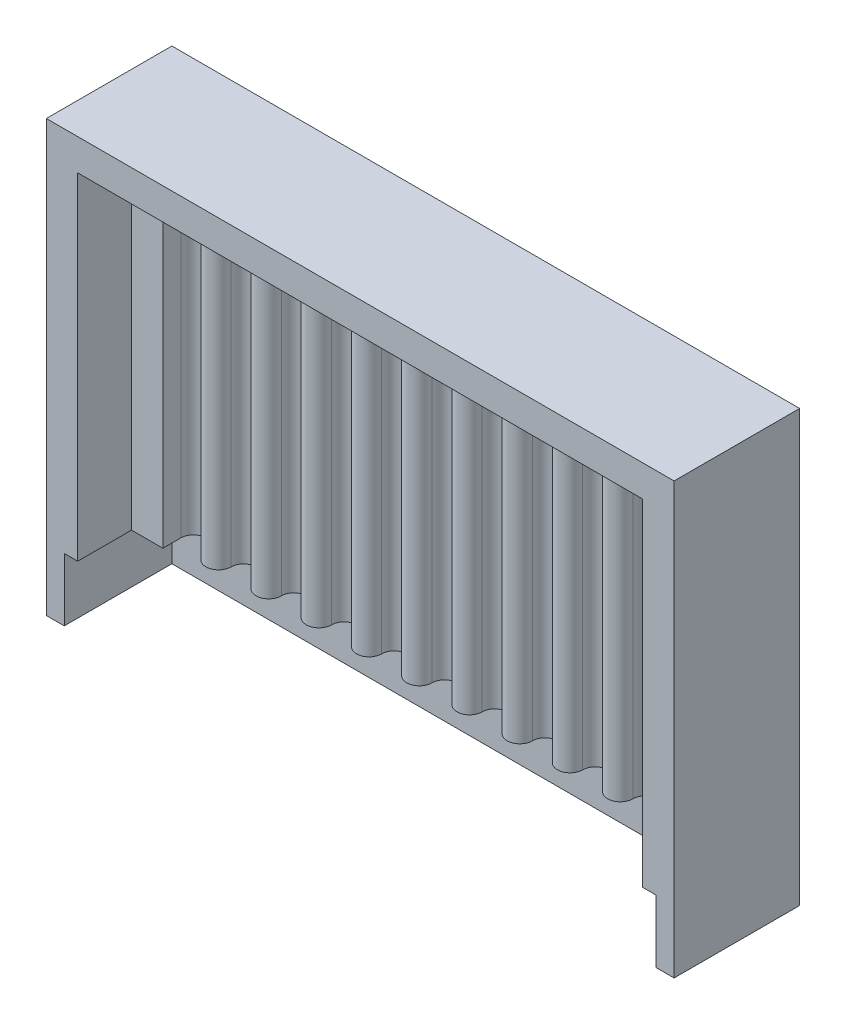
SolidWorks part; units mm, degrees
ref_plane "前视基准面" through (0, 0, 0) normal (0, 0, 1) x (1, 0, 0)
ref_plane "上视基准面" through (0, 0, 0) normal (0, 1, 0) x (1, 0, 0)
ref_plane "右视基准面" through (0, 0, 0) normal (1, 0, 0) x (0, 0, -1)
other "Configuration Table"
sketch "草图1" plane through (0, 0, 0) normal (0, 0, 1) x (1, 0, 0)
  line L1 (-17.5, 12) -> (17.5, 12)
  line L2 (-17.5, 12) -> (-17.5, -12)
  line L3 (-17.5, -12) -> (17.5, -12)
  line L4 (17.5, 12) -> (17.5, -12)
  line L5 (-17.5, 12) -> (17.5, -12) construction
  line L6 (-17.5, -12) -> (17.5, 12) construction
  point P0 (0, 0)
extrude "凸台-拉伸1" add sketch "草图1" along normal blind 7
sketch "草图2" plane through (0, 0, 7) normal (0, 0, 1) x (1, 0, 0)
  line L1 (-15.75, 10.25) -> (15.75, 10.25)
  line L2 (-15.75, 10.25) -> (-15.75, -10.25)
  line L3 (-15.75, -10.25) -> (15.75, -10.25)
  line L4 (15.75, 10.25) -> (15.75, -10.25)
  line L5 (-15.75, 10.25) -> (15.75, -10.25) construction
  line L6 (-15.75, -10.25) -> (15.75, 10.25) construction
  point P0 (0, 0)
  dimension "D1" = 20.5
  dimension "D2" = 31.5
extrude "切除-拉伸1" cut sketch "草图2" against normal blind 3
sketch "草图3" plane through (0, 0, 4) normal (0, 0, 1) x (1, 0, 0)
  line L1 (-14, 8.5) -> (14, 8.5)
  line L2 (-14, 8.5) -> (-14, -8.5)
  line L3 (-14, -8.5) -> (14, -8.5)
  line L4 (14, 8.5) -> (14, -8.5)
  line L5 (-14, 8.5) -> (14, -8.5) construction
  line L6 (-14, -8.5) -> (14, 8.5) construction
  point P0 (0, 0)
extrude "切除-拉伸2" cut sketch "草图3" against normal blind 2
sketch "草图4" plane through (0, 8.5, 0) normal (0, -1, 0) x (1, 0, 0)
  line L0 (-15, 3) -> (-15, 1)
  line L1 (-14, 4) -> (14, 4) construction
  line L2 (-14, 4) -> (-14, 2) construction
  line L3 (-14, 2) -> (14, 2) construction
  line L4 (14, 4) -> (14, 2) construction
  line L5 (-14, 3) -> (-13.6627, 3) construction
  line L6 (-15, 1) -> (15, 1)
  line L7 (15, 1) -> (15, 3)
  line L8 (15, 3) -> (14, 3)
  line L9 (-14, 3) -> (-15, 3)
  arc A0 (-14, 3) -> (-12.6, 3) centre (-13.3, 3) ccw
  arc A1 (-11.2, 3) -> (-12.6, 3) centre (-11.9, 3) ccw
  arc A2 (-8.4, 3) -> (-9.8, 3) centre (-9.1, 3) ccw
  arc A3 (-11.2, 3) -> (-9.8, 3) centre (-10.5, 3) ccw
  arc A4 (-5.6, 3) -> (-7, 3) centre (-6.3, 3) ccw
  arc A5 (-8.4, 3) -> (-7, 3) centre (-7.7, 3) ccw
  arc A6 (-2.8, 3) -> (-4.2, 3) centre (-3.5, 3) ccw
  arc A7 (-5.6, 3) -> (-4.2, 3) centre (-4.9, 3) ccw
  arc A8 (0, 3) -> (-1.4, 3) centre (-0.7, 3) ccw
  arc A9 (-2.8, 3) -> (-1.4, 3) centre (-2.1, 3) ccw
  arc A10 (2.8, 3) -> (1.4, 3) centre (2.1, 3) ccw
  arc A11 (0, 3) -> (1.4, 3) centre (0.7, 3) ccw
  arc A12 (5.6, 3) -> (4.2, 3) centre (4.9, 3) ccw
  arc A13 (2.8, 3) -> (4.2, 3) centre (3.5, 3) ccw
  arc A14 (8.4, 3) -> (7, 3) centre (7.7, 3) ccw
  arc A15 (5.6, 3) -> (7, 3) centre (6.3, 3) ccw
  arc A16 (11.2, 3) -> (9.8, 3) centre (10.5, 3) ccw
  arc A17 (8.4, 3) -> (9.8, 3) centre (9.1, 3) ccw
  arc A18 (14, 3) -> (12.6, 3) centre (13.3, 3) ccw
  arc A19 (11.2, 3) -> (12.6, 3) centre (11.9, 3) ccw
  point P4 (-14, 3)
  point P9 (-13.3, 3)
  point P12 (-11.9, 3)
  dimension "D2" = 1.4
  dimension "D3" = 10
  dimension "D1" = 0.7
  dimension "D4" = 1
  dimension "D5" = 2
  dimension "D6" = 1
extrude "凸台-拉伸2" add sketch "草图4" along normal up to surface (17 mm away) up to face at (0, -8.5, 3)
sketch "草图6" plane through (0, -12, 0) normal (0, -1, 0) x (1, 0, 0)
  line L0 (-16.5, 7) -> (-16.5, 1)
  line L1 (-17.5, 7) -> (17.5, 7) construction
  line L2 (-16.5, 1) -> (16.5, 1)
  line L3 (16.5, 1) -> (16.5, 7)
  line L4 (16.5, 7) -> (-16.5, 7)
  line L5 (-17.5, 7) -> (-17.5, 0) construction
  line L6 (17.5, 7) -> (17.5, 0) construction
  line L7 (-17.5, 0) -> (17.5, 0) construction
  dimension "D1" = 1
  dimension "D2" = 1
  dimension "D3" = 1
extrude "切除-拉伸3" cut sketch "草图6" against normal up to surface (3.5 mm away) up to face at (0, -8.5, 3.087)
